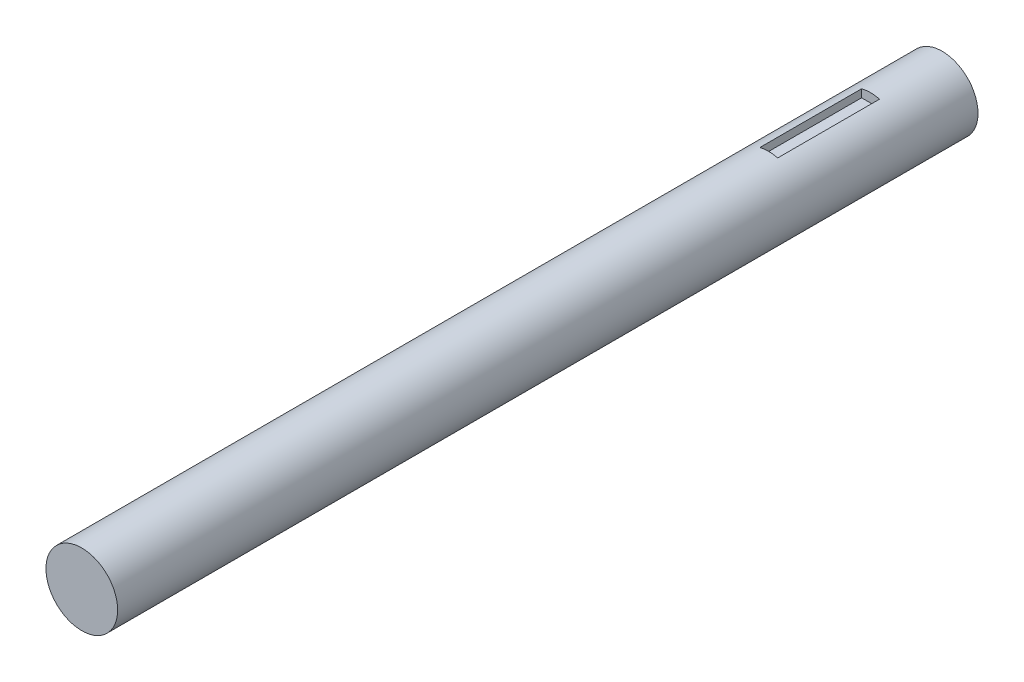
SolidWorks part; units mm, degrees
ref_plane "Front Plane" through (0, 0, 0) normal (0, 0, 1) x (1, 0, 0)
ref_plane "Top Plane" through (0, 0, 0) normal (0, 1, 0) x (1, 0, 0)
ref_plane "Right Plane" through (0, 0, 0) normal (1, 0, 0) x (0, 0, -1)
sketch "Sketch1" plane through (0, 0, 0) normal (0, 0, 1) x (1, 0, 0)
  circle A0 centre (0, 0) radius 6.35
  dimension "D1" = 12.7
extrude "Boss-Extrude1" add sketch "Sketch1" along normal blind 152.4
ref_plane "Plane1" through (0, 0, 12.7) normal (0, 0, -1) x (-1, 0, 0)
sketch "Sketch2" plane through (0, 0, 12.7) normal (0, 0, -1) x (-1, 0, 0)
  line L0 (1.5714, 4.7625) -> (-0.0161, 4.7625)
  line L1 (0, 0) -> (0, 6.35) construction
  line L2 (1.5714, 4.7625) -> (1.5714, 7.9375)
  line L3 (1.5714, 7.9375) -> (-1.6036, 7.9375)
  line L4 (-1.6036, 7.9375) -> (-1.6036, 4.7625)
  line L5 (-0.0161, 4.7625) -> (-1.6036, 4.7625)
  circle A1 centre (0, 0) radius 6.35 construction
  dimension "D1" = 1.5875
  dimension "D2" = 1.5875
  dimension "D3" = 1.5875
  dimension "D4" = 3.175
extrude "Cut-Extrude1" cut sketch "Sketch2" against normal blind 18.034
